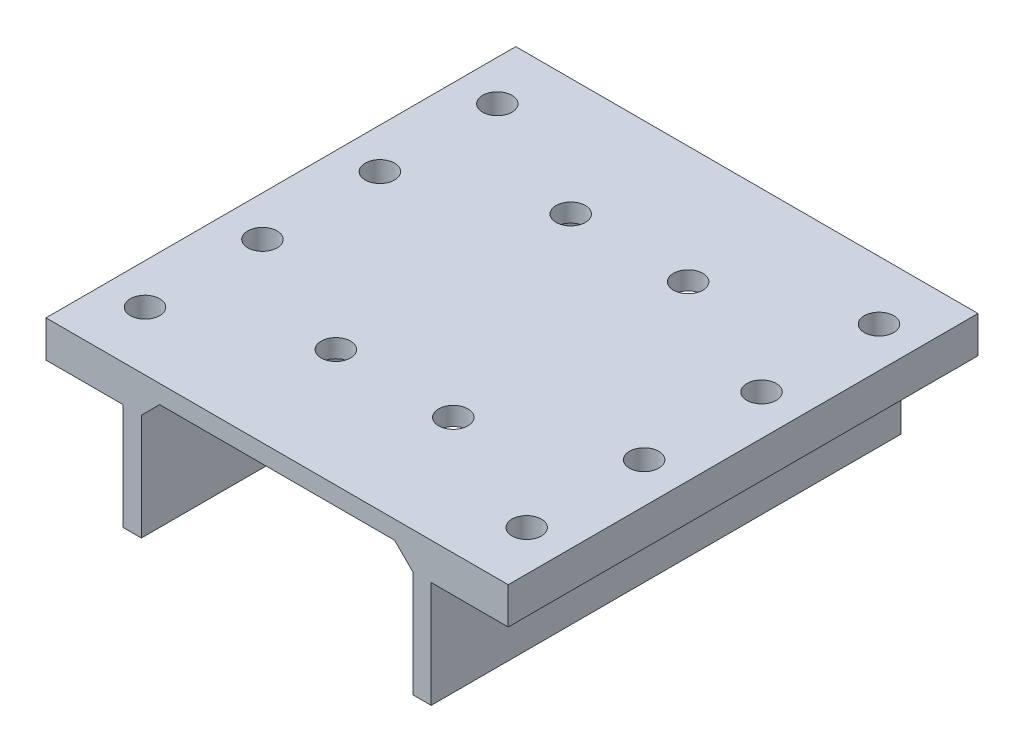
SolidWorks part; units mm, degrees
ref_plane "Front Plane" through (0, 0, 0) normal (0, 0, 1) x (1, 0, 0)
ref_plane "Top Plane" through (0, 0, 0) normal (0, 1, 0) x (1, 0, 0)
ref_plane "Right Plane" through (0, 0, 0) normal (1, 0, 0) x (0, 0, -1)
sketch "Model" plane through (0, 0, 0) normal (0, 0, 1) x (1, 0, 0)
  line L39 (93.1737, 113.3585) -> (97.1361, 117.3209)
  line L40 (93.1737, 90.3461) -> (93.1737, 113.3585)
  line L41 (89.2113, 90.3461) -> (93.1737, 90.3461)
  line L42 (89.2113, 113.3585) -> (89.2113, 90.3461)
  line L43 (72.5489, 113.3585) -> (89.2113, 113.3585)
  line L44 (72.5489, 121.2833) -> (72.5489, 113.3585)
  line L45 (172.5233, 121.2833) -> (72.5489, 121.2833)
  line L46 (172.5233, 113.3585) -> (172.5233, 121.2833)
  line L47 (155.8609, 113.3585) -> (172.5233, 113.3585)
  line L48 (155.8609, 90.3461) -> (155.8609, 113.3585)
  line L49 (151.8985, 90.3461) -> (155.8609, 90.3461)
  line L50 (151.8985, 113.3585) -> (151.8985, 90.3461)
  line L51 (147.9361, 117.3209) -> (151.8985, 113.3585)
  line L52 (97.1361, 117.3209) -> (147.9361, 117.3209)
extrude "Boss-Extrude1" add sketch "Model" along normal blind 101.6
sketch "Sketch2" plane through (0, 121.2833, 0) normal (0, 1, 0) x (1, 0, 0)
  line L0 (122.5361, 0) -> (122.5361, -101.6) construction
  line L1 (172.5233, 0) -> (72.5489, 0) construction
  line L2 (172.5233, -101.6) -> (72.5489, -101.6) construction
  line L3 (72.5489, -101.6) -> (72.5489, 0) construction
  circle A0 centre (163.8111, -12.7) radius 3.175
  circle A1 centre (163.8111, -38.1) radius 3.175
  circle A2 centre (163.8111, -63.5) radius 3.175
  circle A3 centre (163.8111, -88.9) radius 3.175
  circle A4 centre (81.2611, -38.1) radius 3.175
  circle A5 centre (81.2611, -63.5) radius 3.175
  circle A6 centre (81.2611, -88.9) radius 3.175
  circle A7 centre (81.2611, -12.7) radius 3.175
  dimension "D1" = 41.275
  dimension "D2" = 12.7
  dimension "D5" = 6.35
  dimension "D6" = 8.7122
  dimension "D7" = 38.1
  dimension "D3" = 4
  dimension "D4" = 2
extrude "Cut-Extrude1" cut sketch "Sketch2" against normal through all
sketch "Sketch3" plane through (0, 121.2833, 0) normal (0, 1, 0) x (1, 0, 0)
  line L0 (122.5361, 0) -> (122.5361, -101.6) construction
  line L1 (172.5233, 0) -> (72.5489, 0) construction
  line L2 (172.5233, -101.6) -> (72.5489, -101.6) construction
  circle A0 centre (135.2361, -25.4) radius 3.175
  circle A1 centre (109.8361, -25.4) radius 3.175
  circle A2 centre (109.8361, -76.2) radius 3.175
  circle A3 centre (135.2361, -76.2) radius 3.175
  circle A4 centre (163.8111, -38.1) radius 3.175 construction
  dimension "D1" = 12.7
  dimension "D2" = 25.4
  dimension "D3" = 6.35
  dimension "D6" = 53.975
  dimension "D7" = 38.1
  dimension "D4" = 2
  dimension "D5" = 2
extrude "Cut-Extrude2" cut sketch "Sketch3" against normal through all
sketch "Sketch4" plane through (89.2113, 0, 0) normal (-1, 0, 0) x (0, 0, 1)
  line L0 (101.6, 90.3461) -> (0, 90.3461) construction
  line L1 (0, 113.3585) -> (0, 90.3461) construction
  circle A0 centre (25.4, 99.8711) radius 3.175
  circle A1 centre (76.2, 99.8711) radius 3.175
  dimension "D1" = 9.525
  dimension "D2" = 25.4
  dimension "D3" = 6.35
  dimension "D5" = 76.2
  dimension "D4" = 2
extrude "Cut-Extrude3" cut sketch "Sketch4" against normal through all
